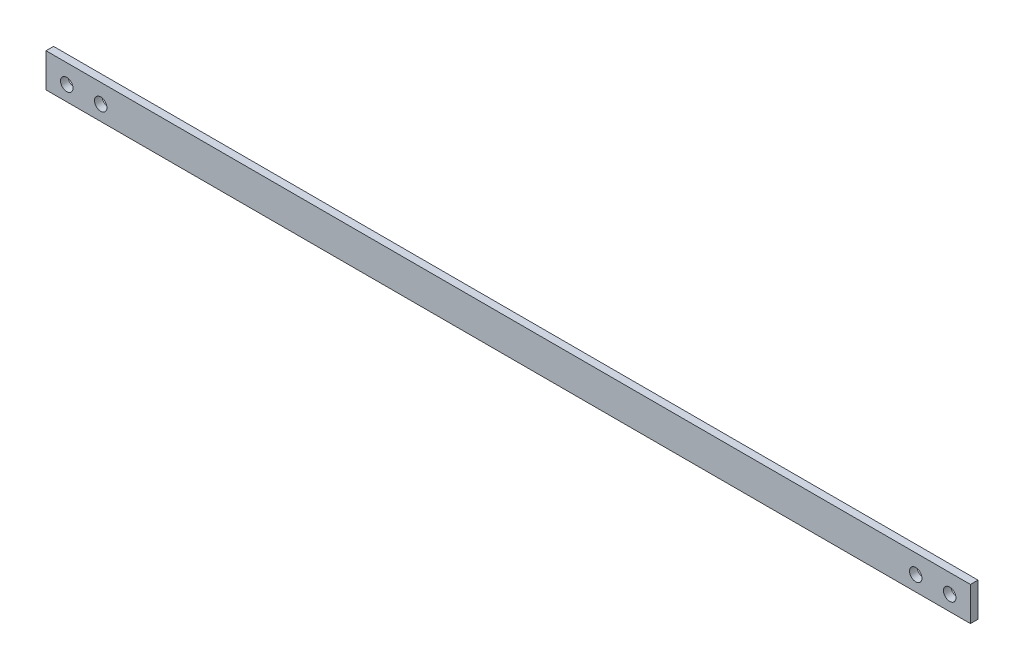
SolidWorks part; units mm, degrees
ref_plane "前视基准面" through (0, 0, 0) normal (0, 0, 1) x (1, 0, 0)
ref_plane "上视基准面" through (0, 0, 0) normal (0, 1, 0) x (1, 0, 0)
ref_plane "右视基准面" through (0, 0, 0) normal (1, 0, 0) x (0, 0, -1)
sketch "草图1" plane through (0, 0, 0) normal (0, 0, 1) x (1, 0, 0)
  line L0 (122.5, 9) -> (122.5, 0) construction
  line L1 (0, 0) -> (245, 0)
  line L2 (0, 0) -> (0, 9)
  line L3 (0, 9) -> (245, 9)
  line L4 (245, 0) -> (245, 9)
  line L5 (10, 0) -> (10, 9) construction
  circle A0 centre (5.5, 4) radius 1.65
  circle A1 centre (14.5, 4) radius 1.65
  circle A2 centre (230.5, 4) radius 1.65
  circle A3 centre (239.5, 4) radius 1.65
  dimension "D4" = 3.3
  dimension "D1" = 245
  dimension "D2" = 9
  dimension "D3" = 9
  dimension "D6" = 5
  dimension "D7" = 10
extrude "凸台-拉伸1" add sketch "草图1" along normal blind 2
